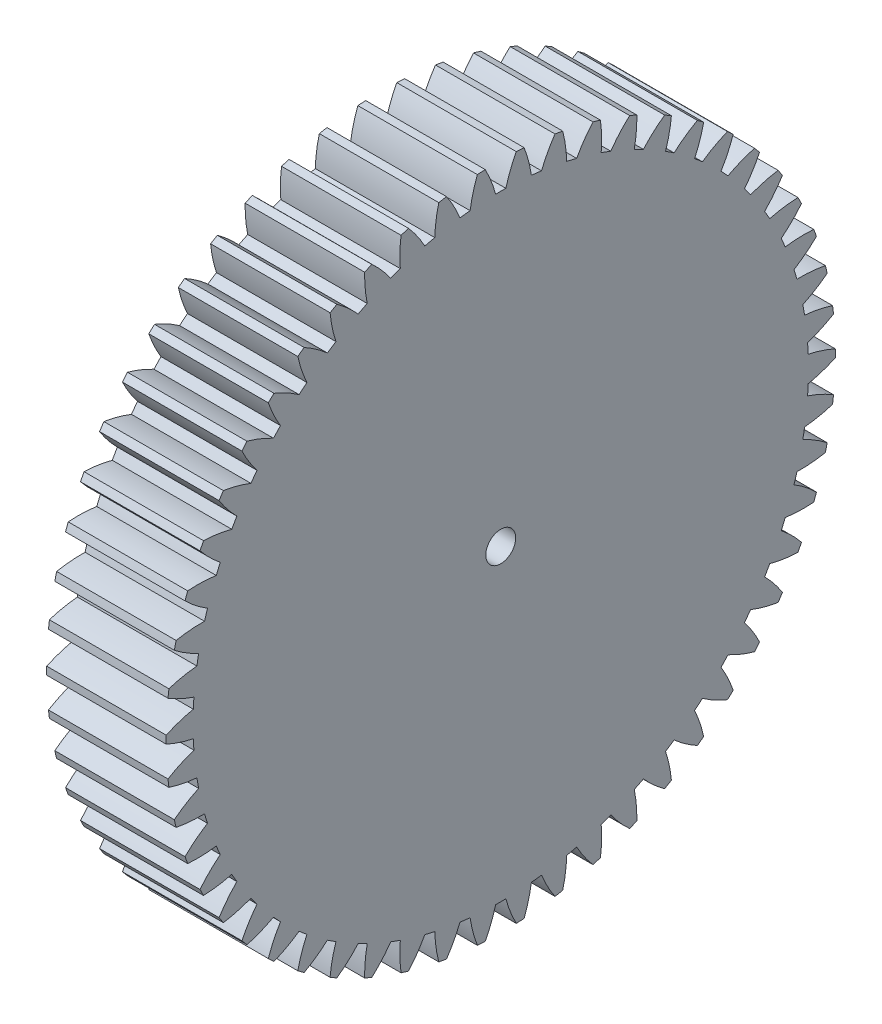
SolidWorks part; units mm, degrees
ref_plane "Plane1" through (0, 0, 0) normal (0, 0, 1) x (1, 0, 0)
ref_plane "Plane2" through (0, 0, 0) normal (0, 1, 0) x (1, 0, 0)
ref_plane "Plane3" through (0, 0, 0) normal (1, 0, 0) x (0, 0, -1)
sketch "HoldingSke" plane through (0, 0, 0) normal (0, 1, 0) x (1, 0, 0)
  line L0 (0, 0) -> (0.2939, -0.4045)
  line L1 (-15, 0) -> (100, 0) construction
  line L2 (0, 0) -> (-2.1039, 2.3779)
  line L3 (0, 0) -> (-11.863, 4.5341)
  line L4 (0, 0) -> (5.0761, 6.9867)
  line L5 (0, 0) -> (-46.8476, -17.4728)
  line L6 (0, 0) -> (-16.5793, -11.1861)
  line L7 (-2.1039, 2.3779) -> (8.6586, 51.2059)
  line L8 (-76.2, 54.61) -> (-75.3, 54.61)
  line L9 (-71.009, 38.7566) -> (-53.1078, 45.2721)
  line L10 (-76.2, 71.12) -> (104.1128, 71.12)
  line L11 (0, 0) -> (-20, 0)
  line L12 (-76.2, 101.6) -> (-76.133, 101.6)
  line L13 (24.9733, 27.94) -> (52.9518, 28.4284)
  line L14 (24.9733, 27.94) -> (24.9743, 27.94)
  line L15 (24.9733, 27.94) -> (100.4006, 29.5858)
  line L16 (-63.627, -2) -> (-12.827, -2)
  circle A0 centre (0, 0) radius 2.5
  circle A1 centre (0, 0) radius 37.5
  circle A2 centre (0, 0) radius 37.5
  circle A3 centre (0, 0) radius 2.5
  dimension "MHD" = 75
  dimension "Hub_dia" = 75
  dimension "Bore" = 5
  dimension "MBD" = 5
  dimension "Num_teeth" = 54
  dimension "Pitch" = 0.5
  dimension "Overall_len" = 50
  dimension "Show_teeth" = 54
  dimension "Thickness" = 20
  dimension "OAL" = 50.0001
  dimension "T_dim" = 0.9
  dimension "Ap" = 20
  dimension "H" = 19.05
  dimension "Pitch_radius" = 180.3128
  dimension "Width" = 20
  dimension "Backlash" = 0.067
  dimension "Addendum_fac" = 1
  dimension "Dedendum_fac" = 1.25
  dimension "Clearance_fac" = 0.25
  dimension "Dedendum_add" = 0.001
  dimension "Module" = 2
sketch "BasProSke" plane through (0, 0, 0) normal (0, 1, 0) x (1, 0, 0)
  line L0 (-10, 0) -> (60, 0) construction
  line L1 (0, 0) -> (0, 56)
  line L2 (0, 0) -> (20, 0)
  line L3 (20, 0) -> (20, 56)
  line L4 (20, 56) -> (0, 56)
  dimension "Thickness" = 20
  dimension "Diameter" = 112
revolve "Base-Revolve" add sketch "BasProSke" angle 360 about L0
sketch "TooCutSke" plane through (0, 0, 0) normal (1, 0, 0) x (0, 0, -1)
  line L1 (0, 0) -> (0, 107) construction
  line L2 (0, 0) -> (-1.6878, 53.9736) construction
  line L3 (0, 0) -> (-6.2774, 107.7782) construction
  line L4 (-1.6878, 53.9736) -> (-3.1387, 53.8891) construction
  arc A0 (0.8539, 51.4919) -> (-0.8539, 51.4919) centre (0, 0) ccw
  arc A1 (2.6145, 55.9644) -> (-2.6145, 55.9644) centre (0, 0) ccw
  circle A2 centre (0, 0) radius 54 construction
  circle A3 centre (0, 0) radius 50.7434 construction
  arc A4 (-0.8539, 51.4919) -> (-2.6145, 55.9644) centre (-21.7083, 45.8655) ccw
  arc A5 (2.6145, 55.9644) -> (0.8539, 51.4919) centre (21.7083, 45.8655) ccw
  dimension "Root_dia" = 102.998
  dimension "Overcut_dia" = 112.0508
  dimension "Pitch_dia" = 108
  dimension "Base_dia" = 101.4868
  dimension "Flank_rad" = 21.6
  dimension "Half_ang" = 3.333
  dimension "Half_CT" = 1.4533
extrude "ToothCut" cut sketch "TooCutSke" along normal through all
fillet "Breaks" [suppressed] radius 0.04
fillet "RootFillets" [suppressed] radius 0.501
pattern_circular "TeethCuts" count 54 every 6.667 about axis through (-10, 0, 0) along (1, 0, 0) of "ToothCut", "RootFillets", "Breaks"
sketch "HubNeaOneSke" plane through (0, 0, 0) normal (-1, 0, 0) x (0, 0, 1)
  circle A0 centre (0, 0) radius 37.5
  dimension "Diameter" = 75
extrude "HubNearOne" [suppressed] add sketch "HubNeaOneSke" along normal blind 30.0001
sketch "HubNeaBotSke" plane through (0, 0, 0) normal (-1, 0, 0) x (0, 0, 1)
  circle A0 centre (0, 0) radius 37.5
  dimension "Diameter" = 75
extrude "HubNearBoth" [suppressed] add sketch "HubNeaBotSke" along normal blind 15
ref_plane "FarPln" through (20, 0, 0) normal (1, 0, 0) x (0, 0, -1)
sketch "HubFarSke" plane through (20, 0, 0) normal (1, 0, 0) x (0, 0, -1)
  circle A0 centre (0, 0) radius 37.5
  dimension "Diameter" = 75
extrude "HubFar" [suppressed] add sketch "HubFarSke" along normal blind 15
sketch "BorSke" plane through (0, 0, 0) normal (1, 0, 0) x (0, 0, -1)
  circle A0 centre (0, 0) radius 2.5
  dimension "Diameter" = 5
extrude "Bore" cut sketch "BorSke" along normal mid plane 100.0001
sketch "KeySke" plane through (0, 0, 0) normal (1, 0, 0) x (0, 0, -1)
  line L0 (-1, 0) -> (-1, 3.4)
  line L1 (-1, 3.4) -> (1, 3.4)
  line L2 (1, 3.4) -> (1, 0)
  line L3 (0, 0) -> (0, 34) construction
  line L4 (-1, 0) -> (1, 0)
  dimension "Offset" = 3.4
extrude "Keyway" [suppressed] cut sketch "KeySke" along normal mid plane 100.0001
pattern_circular "Keyway2" [suppressed] count 2 every 90 about axis through (-10, 0, 0) along (1, 0, 0)
equation "' \"Module@HoldingSke\" = 6.35"
equation "' \"Num_teeth@HoldingSke\" = 12"
equation "' \"Ap@HoldingSke\" =  20"
equation "' \"Ap@HoldingSke\" = 20"
equation "' \"Width@HoldingSke\" = 0.5 * 25.4"
equation "' \"Hub_dia@HoldingSke\"= 1 * 25.4"
equation "' \"Hub_dia@HoldingSke\" = 1 * 25.4"
equation "' \"Overall_len@HoldingSke\" = 1.0 * 25.4"
equation "' \"Bore@HoldingSke\" = 0.75 * 25.4"
equation "' \"T_dim@HoldingSke\" = 0.1 * 25.4"
equation "' \"Width@KeySke\" = 0.25 * 25.4"
equation "' \"Show_teeth@HoldingSke\" = 13"
equation "' \"Backlash@HoldingSke\" = 0.009 * 25.4"
equation "' \"Addendum_fac@HoldingSke\" = 1.0"
equation "' \"Dedendum_fac@HoldingSke\" = 1.25"
equation "' \"Dedendum_add@HoldingSke\" = 0.00005 * 25.4"
equation "' \"Clearance_fac@HoldingSke\" = 0.25"
equation "\"Pitch@HoldingSke\" = 1 / \"Module@HoldingSke\""
equation "\"Overcut_dia@TooCutSke\" = (\"Num_teeth@HoldingSke\" + 2 * \"Addendum_fac@HoldingSke\") / \"Pitch@HoldingSke\" + 0.002 * 25.4"
equation "\"Pitch_dia@TooCutSke\" = \"Num_teeth@HoldingSke\" / \"Pitch@HoldingSke\""
equation "\"Base_dia@TooCutSke\" = \"Num_teeth@HoldingSke\" / \"Pitch@HoldingSke\" * cos((\"Ap@HoldingSke\"  * 3.14159265 / 180))"
equation "\"Root_dia@TooCutSke\" = (\"Num_teeth@HoldingSke\" + 2) / \"Pitch@HoldingSke\" - 2 * (\"Addendum_fac@HoldingSke\" + \"Dedendum_fac@HoldingSke\") / \"Pitch@HoldingSke\" - \"Dedendum_add@HoldingSke\" * 2"
equation "\"Half_ang@TooCutSke\" = 180 / \"Num_teeth@HoldingSke\""
equation "\"Half_CT@TooCutSke\" = \"Num_teeth@HoldingSke\" / \"Pitch@HoldingSke\" * sin((3.14159265 / 2 / \"Num_teeth@HoldingSke\")) / 2 - 7 * \"Backlash@HoldingSke\" / 4"
equation "\"Flank_rad@TooCutSke\" = \"Num_teeth@HoldingSke\" / \"Pitch@HoldingSke\" / 5"
equation "\"Radius@RootFillets\" = \"Clearance_fac@HoldingSke\" / \"Pitch@HoldingSke\" + \"Dedendum_add@HoldingSke\""
equation "\"Break_rad@Breaks\" = 0.02 / \"Pitch@HoldingSke\""
equation "\"Thickness@HoldingSke\" = \"Width@HoldingSke\""
equation "\"OAL@HoldingSke\" = \"Thickness@HoldingSke\""
equation "\"MHD@HoldingSke\" = (\"Num_teeth@HoldingSke\" + 2) / \"Pitch@HoldingSke\" - 2 * (\"Addendum_fac@HoldingSke\" + \"Dedendum_fac@HoldingSke\")  / \"Pitch@HoldingSke\" - \"Dedendum_add@HoldingSke\" * 2"
equation "\"MBD@HoldingSke\" = (\"Num_teeth@HoldingSke\" + 2) / \"Pitch@HoldingSke\" - 2 * (\"Addendum_fac@HoldingSke\" + \"Dedendum_fac@HoldingSke\")  / \"Pitch@HoldingSke\" - \"Dedendum_add@HoldingSke\" * 2 - 0.002 * 25.4"
equation "\"MHD@HoldingSke\" = ((sgn( \"MHD@HoldingSke\" - \"Hub_dia@HoldingSke\" )-1)*( \"MHD@HoldingSke\" - \"Hub_dia@HoldingSke\" ))/-2+ \"Hub_dia@HoldingSke\""
equation "\"MBD@HoldingSke\" = ((sgn( \"MBD@HoldingSke\" - \"Bore@HoldingSke\" )-1)*( \"MBD@HoldingSke\" - \"Bore@HoldingSke\" ))/-2+ \"Bore@HoldingSke\""
equation "\"OAL@HoldingSke\" = ((sgn( \"OAL@HoldingSke\" - \"Overall_len@HoldingSke\" )+1)*( \"OAL@HoldingSke\" - \"Overall_len@HoldingSke\" ))/2 + \"Overall_len@HoldingSke\" + 0.000002 * 25.4"
equation "\"Num_teeth@TeethCuts\" = int( \"Show_teeth@HoldingSke\" ) + 1"
equation "\"Num_teeth@TeethCuts\" = ((sgn( \"Num_teeth@TeethCuts\" - \"Num_teeth@HoldingSke\" )-1)*( \"Num_teeth@TeethCuts\" - \"Num_teeth@HoldingSke\" ))/-2+ \"Num_teeth@HoldingSke\""
equation "\"Num_teeth@TeethCuts\" = ((sgn( \"Num_teeth@TeethCuts\" - 2.0)+1)*( \"Num_teeth@TeethCuts\" - 2.0))/2 +2.0"
equation "\"Angle@TeethCuts\" = 360.0 / \"Num_teeth@HoldingSke\""
equation "\"Diameter@BasProSke\" = (\"Num_teeth@HoldingSke\" + 2 * \"Addendum_fac@HoldingSke\") / \"Pitch@HoldingSke\""
equation "\"Thickness@BasProSke\"  = \"Thickness@HoldingSke\""
equation "' \"Fillet_rad@BasProSke\" =  \"Thickness@HoldingSke\" * 0.05"
equation "' \"Fillet_rad@BasProSke\" = \"Thickness@HoldingSke\" * 0.05"
equation "\"MHD@HoldingSke\" = ((sgn( \"MHD@HoldingSke\" - \"Root_dia@TooCutSke\" )-1)*( \"MHD@HoldingSke\" - \"Root_dia@TooCutSke\" ))/-2+ \"Root_dia@TooCutSke\""
equation "\"Diameter@HubNeaOneSke\" = \"MHD@HoldingSke\""
equation "\"Length@HubNearOne\" = \"OAL@HoldingSke\" - \"Thickness@BasProSke\""
equation "\"Diameter@HubNeaBotSke\" = \"MHD@HoldingSke\""
equation "\"Length@HubNearBoth\" = ( \"OAL@HoldingSke\" - \"Thickness@BasProSke\" ) / 2.0"
equation "\"Thickness@FarPln\" = \"Thickness@BasProSke\""
equation "\"Diameter@HubFarSke\" = \"MHD@HoldingSke\""
equation "\"Length@HubFar\" = ( \"OAL@HoldingSke\" - \"Thickness@BasProSke\" ) / 2.0"
equation "\"Diameter@BorSke\" = \"MBD@HoldingSke\""
equation "\"D1@Bore\" = \"OAL@HoldingSke\" * 2.0"
equation "\"D1@Keyway\" = \"OAL@HoldingSke\" * 2.0"
equation "\"Offset@KeySke\" = \"T_dim@HoldingSke\" + \"MBD@HoldingSke\" / 2.0"
